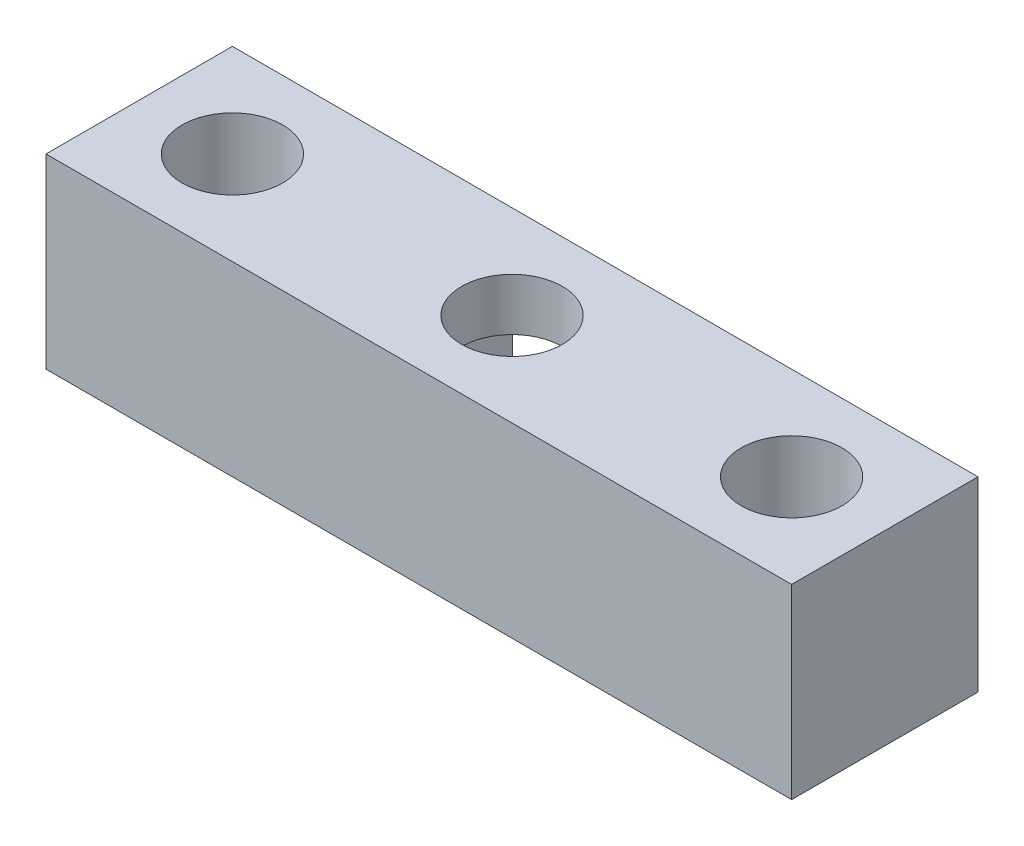
SolidWorks part; units mm, degrees
ref_plane "Front Plane" through (0, 0, 0) normal (0, 0, 1) x (1, 0, 0)
ref_plane "Top Plane" through (0, 0, 0) normal (0, 1, 0) x (1, 0, 0)
ref_plane "Right Plane" through (0, 0, 0) normal (1, 0, 0) x (0, 0, -1)
sketch "Sketch1" plane through (0, 0, 0) normal (0, 1, 0) x (1, 0, 0)
  line L1 (-25.4, 12.7) -> (25.4, 12.7)
  line L2 (-25.4, 12.7) -> (-25.4, 0)
  line L3 (-25.4, 0) -> (25.4, 0)
  line L4 (25.4, 12.7) -> (25.4, 0)
  point P4 (0, 0)
  dimension "D1" = 50.8
  dimension "D2" = 12.7
extrude "Boss-Extrude1" add sketch "Sketch1" along normal blind 12.7
sketch "Sketch2" plane through (0, 12.7, 0) normal (0, 1, 0) x (1, 0, 0)
  line L0 (-25.4, 6.35) -> (25.4, 6.35) construction
  line L1 (-25.4, 12.7) -> (-25.4, 0) construction
  line L2 (25.4, 0) -> (25.4, 12.7) construction
  circle A0 centre (-19.05, 6.35) radius 3.429
  circle A1 centre (19.05, 6.35) radius 3.429
  circle A2 centre (0, 6.35) radius 3.429
  dimension "D1" = 6.858
  dimension "D2" = 6.35
  dimension "D3" = 6.35
extrude "Cut-Extrude1" cut sketch "Sketch2" against normal through all
ref_plane "Plane1" through (0, 6.35, 0) normal (0, 1, 0) x (1, 0, 0)
sketch "Sketch3" plane through (0, 6.35, 0) normal (0, 1, 0) x (1, 0, 0)
  line L0 (-6.3058, 6.35) -> (-6.3058, 19.3961)
  line L1 (-3.1529, 0.889) -> (3.1529, 0.889)
  line L2 (3.1529, 0.889) -> (6.3058, 6.35)
  line L3 (6.3058, 6.35) -> (3.1529, 11.811) construction
  line L4 (3.1529, 11.811) -> (-3.1529, 11.811) construction
  line L5 (-3.1529, 11.811) -> (-6.3058, 6.35) construction
  line L6 (-6.3058, 6.35) -> (-3.1529, 0.889)
  line L7 (-6.3058, 19.3961) -> (6.3058, 19.3961)
  line L8 (6.3058, 19.3961) -> (6.3058, 6.35)
  circle A0 centre (0, 6.35) radius 5.461 construction
  dimension "D1" = 10.922
extrude "Cut-Extrude2" cut sketch "Sketch3" against normal mid plane 5.588
